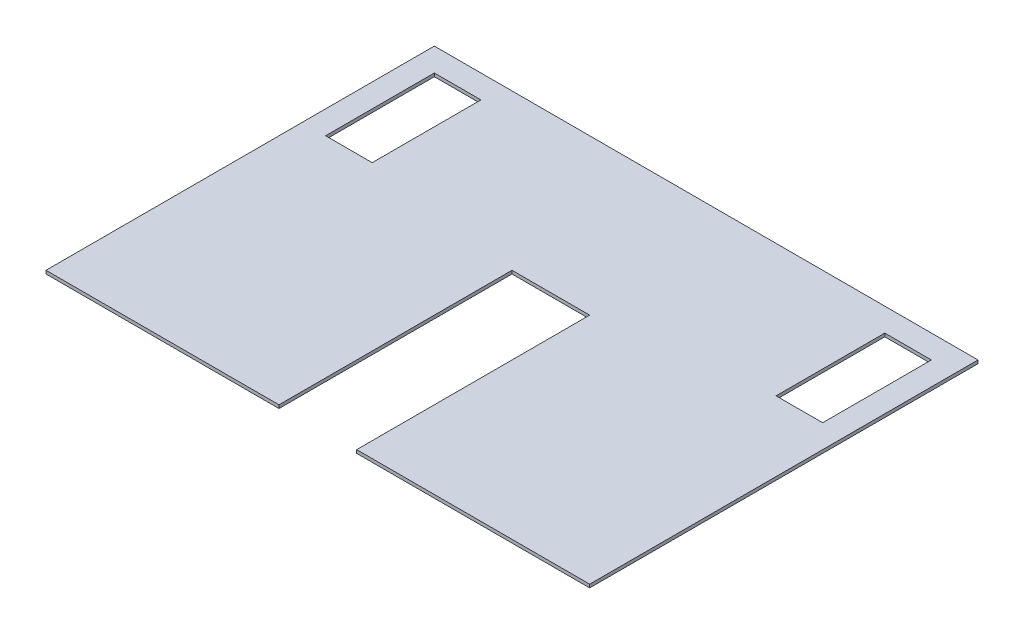
SolidWorks part; units mm, degrees
material "6061-T6 (SS)"
ref_plane "Front" through (0, 0, 0) normal (0, 0, 1) x (1, 0, 0)
ref_plane "Top" through (0, 0, 0) normal (0, 1, 0) x (1, 0, 0)
ref_plane "Right" through (0, 0, 0) normal (1, 0, 0) x (0, 0, -1)
sketch "Sketch1" plane through (0, 0, 0) normal (0, 1, 0) x (1, 0, 0)
  line L1 (0, 0) -> (-177.8, 0)
  line L2 (0, 0) -> (0, 127)
  line L3 (0, 127) -> (-177.8, 127)
  line L4 (-177.8, 0) -> (-177.8, 127)
  dimension "D1" = 177.8
  dimension "D2" = 127
extrude "Boss-Extrude1" add sketch "Sketch1" along normal blind 1.0668
sketch "Sketch2" plane through (0, 1.0668, 0) normal (0, 1, 0) x (1, 0, 0)
  line L0 (-101.6, 82.55) -> (-101.6, 0) construction
  line L1 (-101.6, 76.2) -> (-30.4728, 76.2) construction
  line L3 (-76.2, 82.55) -> (-76.2, 0) construction
  line L6 (-177.8, 0) -> (0, 0) construction
  line L10 (-24.13, 127) -> (-24.13, 76.2) construction
  line L15 (-24.13, 82.55) -> (0, 82.55) construction
  line L21 (-6.35, 120.65) -> (-6.35, 82.55) construction
  line L28 (0, 120.65) -> (-24.13, 120.65) construction
  line L36 (-177.8, 82.55) -> (-153.67, 82.55) construction
  line L45 (-171.45, 120.65) -> (-171.45, 82.55) construction
  line L55 (-153.67, 76.2) -> (-153.67, 127) construction
  line L66 (-153.67, 120.65) -> (-177.8, 120.65) construction
  line L78 (-171.45, 120.65) -> (-171.45, 82.55) construction
  line L79 (-171.45, 82.55) -> (-153.67, 82.55) construction
  line L80 (-153.67, 82.55) -> (-153.67, 120.65) construction
  line L81 (-153.67, 120.65) -> (-171.45, 120.65) construction
  line L82 (-101.6, 76.2) -> (-101.6, 0)
  line L83 (-76.2, 76.2) -> (-76.2, 0)
  line L84 (-101.6, 76.2) -> (-76.2, 76.2)
  line L85 (-101.6, 0) -> (-76.2, 0)
  line L86 (-6.35, 120.65) -> (-6.35, 82.55) construction
  line L87 (-24.13, 120.65) -> (-24.13, 82.55) construction
  line L88 (-24.13, 82.55) -> (-6.35, 82.55) construction
  line L89 (-6.35, 120.65) -> (-24.13, 120.65) construction
  line L90 (-170.18, 83.82) -> (-154.94, 83.82)
  line L91 (-154.94, 83.82) -> (-154.94, 119.38)
  line L92 (-154.94, 119.38) -> (-170.18, 119.38)
  line L93 (-170.18, 119.38) -> (-170.18, 83.82)
  line L94 (-22.86, 119.38) -> (-22.86, 83.82)
  line L95 (-22.86, 83.82) -> (-7.62, 83.82)
  line L96 (-7.62, 119.38) -> (-7.62, 83.82)
  line L97 (-7.62, 119.38) -> (-22.86, 119.38)
  dimension "D1" = 1.27
extrude "Cut-Extrude1" cut sketch "Sketch2" against normal through all
